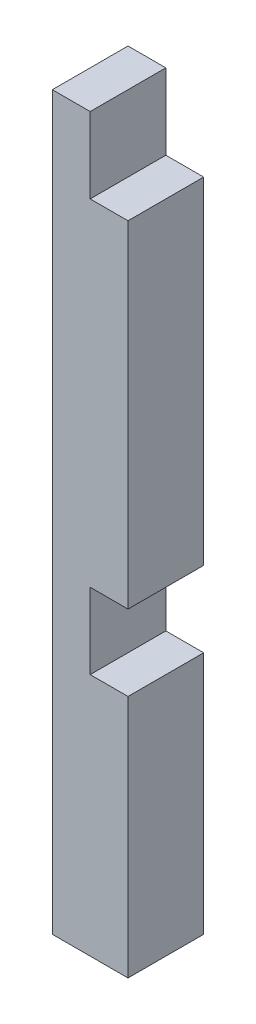
SolidWorks part; units mm, degrees
ref_plane "Front Plane" through (0, 0, 0) normal (0, 0, 1) x (1, 0, 0)
ref_plane "Top Plane" through (0, 0, 0) normal (0, 1, 0) x (1, 0, 0)
ref_plane "Right Plane" through (0, 0, 0) normal (1, 0, 0) x (0, 0, -1)
sketch "Sketch2" plane through (0, 0, 0) normal (0, 1, 0) x (1, 0, 0)
  line L1 (0, 0) -> (90, 0)
  line L2 (0, 0) -> (0, 90)
  line L3 (0, 90) -> (90, 90)
  line L4 (90, 0) -> (90, 90)
  dimension "D1" = 90
  dimension "D2" = 90
extrude "Boss-Extrude1" add sketch "Sketch2" along normal blind 870
sketch "Sketch3" plane through (90, 0, 0) normal (1, 0, 0) x (0, 0, -1)
  line L0 (90, 870) -> (90, 0) construction
  line L1 (0, 870) -> (90, 870)
  line L2 (0, 870) -> (0, 780)
  line L3 (0, 780) -> (90, 780)
  line L4 (90, 870) -> (90, 780)
  line L5 (0, 870) -> (0, 0) construction
  line L6 (0, 290) -> (90, 290)
  line L7 (0, 290) -> (0, 380)
  line L8 (0, 380) -> (90, 380)
  line L9 (90, 290) -> (90, 380)
  line L10 (0, 0) -> (90, 0) construction
  dimension "D1" = 90
  dimension "D2" = 90
  dimension "D3" = 290
extrude "Cut-Extrude1" cut sketch "Sketch3" against normal blind 45
